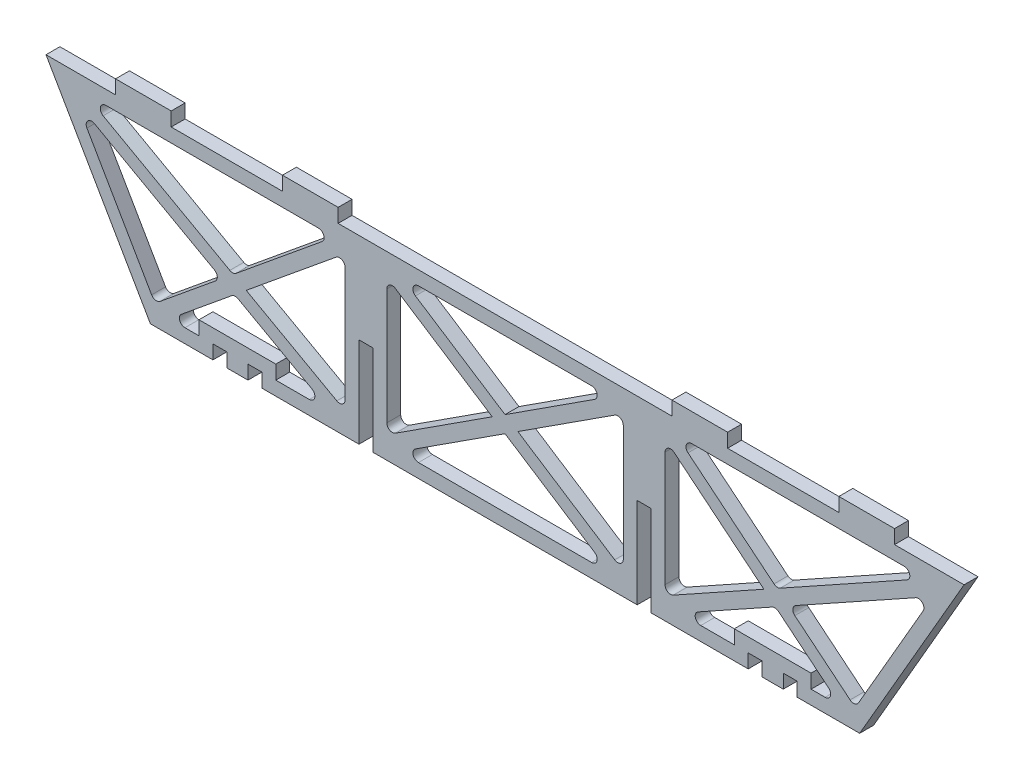
SolidWorks part; units mm, degrees
ref_plane "Front Plane" through (0, 0, 0) normal (0, 0, 1) x (1, 0, 0)
ref_plane "Top Plane" through (0, 0, 0) normal (0, 1, 0) x (1, 0, 0)
ref_plane "Right Plane" through (0, 0, 0) normal (1, 0, 0) x (0, 0, -1)
sketch "Sketch1" plane through (0, 0, 0) normal (0, 0, 1) x (1, 0, 0)
  line L0 (47.6603, 0) -> (76.2, 0)
  line L1 (0, 0) -> (0, 82.55) construction
  line L2 (0, 82.55) -> (31.75, 82.55)
  line L3 (98.552, 0) -> (142.875, 0)
  line L4 (0, 82.55) -> (47.6603, 0)
  line L5 (209.55, 82.55) -> (209.55, 0) construction
  line L6 (146.05, 82.55) -> (146.05, 41.275) construction
  line L7 (0, 0) -> (47.6603, 0) construction
  line L8 (142.875, 0) -> (142.875, 41.275)
  line L9 (31.75, 82.55) -> (31.75, 88.9)
  line L10 (31.75, 88.9) -> (57.15, 88.9)
  line L11 (57.15, 88.9) -> (57.15, 82.55)
  line L12 (57.15, 82.55) -> (107.95, 82.55)
  line L13 (107.95, 82.55) -> (107.95, 88.9)
  line L14 (107.95, 88.9) -> (133.35, 88.9)
  line L15 (133.35, 88.9) -> (133.35, 82.55)
  line L16 (133.35, 82.55) -> (209.55, 82.55)
  line L17 (170.0204, 6.35) -> (249.0796, 6.35)
  line L18 (155.575, 14.8006) -> (155.575, 67.7494)
  line L19 (170.0204, 76.2) -> (249.0796, 76.2)
  line L20 (136.525, 14.3036) -> (136.525, 66.7274)
  line L21 (104.902, 6.35) -> (120.207, 6.35)
  line L22 (104.902, 12.7) -> (104.902, 6.35)
  line L23 (69.85, 12.7) -> (104.902, 12.7)
  line L24 (69.85, 12.7) -> (69.85, 6.35)
  line L25 (76.2, 0) -> (76.2, 6.35)
  line L26 (76.2, 6.35) -> (82.55, 6.35)
  line L27 (82.55, 6.35) -> (82.55, 0)
  line L28 (82.55, 0) -> (92.202, 0)
  line L29 (92.202, 0) -> (92.202, 6.35)
  line L30 (92.202, 6.35) -> (98.552, 6.35)
  line L31 (98.552, 6.35) -> (98.552, 0)
  line L32 (10.9985, 76.2) -> (136.525, 6.35) construction
  line L33 (51.3264, 6.35) -> (136.525, 76.2) construction
  line L34 (155.575, 6.35) -> (209.55, 41.275) construction
  line L35 (155.575, 76.2) -> (209.55, 41.275) construction
  line L36 (63.4386, 6.35) -> (69.85, 6.35)
  line L37 (18.6834, 62.8895) -> (48.2215, 11.728)
  line L38 (27.3165, 76.2) -> (124.4128, 76.2)
  line L39 (26.0814, 71.4405) -> (83.9206, 39.2555)
  line L40 (142.875, 41.275) -> (149.225, 41.275)
  line L41 (22.1181, 66.379) -> (76.8867, 35.9027)
  line L42 (126.0232, 71.6958) -> (86.766, 39.5108)
  line L43 (149.225, 0) -> (149.225, 41.275)
  line L44 (149.225, 0) -> (209.55, 0)
  line L45 (61.8282, 10.8542) -> (84.7804, 29.6715)
  line L46 (159.4949, 12.6681) -> (203.7056, 41.275)
  line L47 (159.4949, 69.8819) -> (203.7056, 41.275)
  line L48 (168.6406, 71.5275) -> (209.55, 45.0567)
  line L49 (168.6406, 11.0225) -> (209.55, 37.4933)
  line L50 (136.525, 6.35) -> (136.525, 47.625) construction
  line L51 (91.3963, 35.0956) -> (132.3746, 68.6917)
  line L52 (136.525, 47.625) -> (155.575, 47.625) construction
  line L53 (155.575, 6.35) -> (155.575, 47.625) construction
  line L54 (51.3264, 6.35) -> (69.85, 6.35) construction
  line L55 (10.9985, 76.2) -> (51.3264, 6.35) construction
  line L56 (77.262, 31.7189) -> (52.0316, 11.0337)
  line L57 (91.3963, 35.0956) -> (132.7499, 12.0841)
  line L58 (87.6258, 29.9268) -> (121.4421, 11.1095)
  line L59 (136.525, 66.7274) -> (136.525, 76.2) construction
  line L60 (114.3, 82.55) -> (127, 82.55) construction
  line L61 (114.3, 76.2) -> (114.3, 82.55) construction
  line L62 (127, 82.55) -> (127, 76.2) construction
  line L63 (38.1, 82.55) -> (50.8, 82.55) construction
  line L64 (50.8, 82.55) -> (50.8, 76.2) construction
  line L65 (38.1, 76.2) -> (38.1, 82.55) construction
  line L66 (50.8, 76.2) -> (114.3, 76.2) construction
  line L67 (10.9985, 76.2) -> (38.1, 76.2) construction
  line L68 (127, 76.2) -> (209.55, 76.2) construction
  line L69 (87.376, 12.7) -> (104.902, 12.7) construction
  line L70 (87.376, 12.7) -> (87.376, 12.7) construction
  line L71 (87.376, 12.7) -> (87.376, 12.7) construction
  line L72 (87.376, 12.7) -> (87.376, 12.7) construction
  line L73 (69.85, 12.7) -> (87.376, 12.7) construction
  line L74 (104.902, 6.35) -> (136.525, 6.35) construction
  line L75 (155.575, 6.35) -> (209.55, 6.35) construction
  line L76 (136.525, 76.2) -> (124.4128, 76.2) construction
  line L77 (27.3165, 76.2) -> (10.9985, 76.2) construction
  line L78 (10.9985, 76.2) -> (18.6834, 62.8895) construction
  line L79 (104.902, 12.7) -> (104.902, 6.35) construction
  line L80 (69.85, 6.35) -> (69.85, 12.7) construction
  line L81 (155.575, 76.2) -> (170.0204, 76.2) construction
  line L82 (155.575, 76.2) -> (155.575, 67.7494) construction
  line L83 (331.4742, 29.9268) -> (297.6579, 11.1095)
  line L84 (327.7037, 35.0956) -> (286.3501, 12.0841)
  line L85 (341.838, 31.7189) -> (367.0684, 11.0337)
  line L86 (327.7037, 35.0956) -> (286.7254, 68.6917)
  line L87 (250.4594, 11.0225) -> (209.55, 37.4933)
  line L88 (250.4594, 71.5275) -> (209.55, 45.0567)
  line L89 (259.6051, 69.8819) -> (215.3944, 41.275)
  line L90 (259.6051, 12.6681) -> (215.3944, 41.275)
  line L91 (357.2718, 10.8542) -> (334.3196, 29.6715)
  line L92 (269.875, 0) -> (209.55, 0)
  line L93 (269.875, 0) -> (269.875, 41.275)
  line L94 (293.0768, 71.6958) -> (332.334, 39.5108)
  line L95 (396.9819, 66.379) -> (342.2133, 35.9027)
  line L96 (276.225, 41.275) -> (269.875, 41.275)
  line L97 (393.0186, 71.4405) -> (335.1794, 39.2555)
  line L98 (391.7835, 76.2) -> (294.6872, 76.2)
  line L99 (400.4166, 62.8895) -> (370.8785, 11.728)
  line L100 (355.6614, 6.35) -> (349.25, 6.35)
  line L101 (320.548, 6.35) -> (320.548, 0)
  line L102 (326.898, 6.35) -> (320.548, 6.35)
  line L103 (326.898, 0) -> (326.898, 6.35)
  line L104 (336.55, 0) -> (326.898, 0)
  line L105 (336.55, 6.35) -> (336.55, 0)
  line L106 (342.9, 6.35) -> (336.55, 6.35)
  line L107 (342.9, 0) -> (342.9, 6.35)
  line L108 (349.25, 12.7) -> (349.25, 6.35)
  line L109 (349.25, 12.7) -> (314.198, 12.7)
  line L110 (314.198, 12.7) -> (314.198, 6.35)
  line L111 (314.198, 6.35) -> (298.893, 6.35)
  line L112 (282.575, 14.3036) -> (282.575, 66.7274)
  line L113 (263.525, 14.8006) -> (263.525, 67.7494)
  line L114 (285.75, 82.55) -> (209.55, 82.55)
  line L115 (285.75, 88.9) -> (285.75, 82.55)
  line L116 (311.15, 88.9) -> (285.75, 88.9)
  line L117 (311.15, 82.55) -> (311.15, 88.9)
  line L118 (361.95, 82.55) -> (311.15, 82.55)
  line L119 (361.95, 88.9) -> (361.95, 82.55)
  line L120 (387.35, 88.9) -> (361.95, 88.9)
  line L121 (387.35, 82.55) -> (387.35, 88.9)
  line L122 (276.225, 0) -> (276.225, 41.275)
  line L123 (419.1, 82.55) -> (371.4397, 0)
  line L124 (320.548, 0) -> (276.225, 0)
  line L125 (419.1, 82.55) -> (387.35, 82.55)
  line L126 (371.4397, 0) -> (342.9, 0)
  line L127 (155.575, 14.8006) -> (155.575, 6.35) construction
  line L128 (155.575, 6.35) -> (170.0204, 6.35) construction
  line L129 (48.2215, 11.728) -> (51.3264, 6.35) construction
  line L130 (51.3264, 6.35) -> (63.4386, 6.35) construction
  line L131 (120.207, 6.35) -> (136.525, 6.35) construction
  line L132 (136.525, 6.35) -> (136.525, 14.3036) construction
  arc A0 (27.3165, 76.2) -> (26.0814, 71.4405) centre (27.3165, 73.66) ccw
  arc A1 (18.6834, 62.8895) -> (22.1181, 66.379) centre (20.8831, 64.1595) cw
  arc A2 (48.2215, 11.728) -> (52.0316, 11.0337) centre (50.4212, 12.998) ccw
  arc A3 (63.4386, 6.35) -> (61.8282, 10.8542) centre (63.4386, 8.89) cw
  arc A4 (86.766, 39.5108) -> (83.9206, 39.2555) centre (85.1556, 41.475) cw
  arc A5 (76.8867, 35.9027) -> (77.262, 31.7189) centre (75.6516, 33.6832) cw
  arc A6 (87.6258, 29.9268) -> (84.7804, 29.6715) centre (86.3908, 27.7073) ccw
  arc A7 (121.4421, 11.1095) -> (120.207, 6.35) centre (120.207, 8.89) cw
  arc A8 (136.525, 14.3036) -> (132.7499, 12.0841) centre (133.985, 14.3036) cw
  arc A9 (136.525, 66.7274) -> (132.3746, 68.6917) centre (133.985, 66.7274) ccw
  arc A10 (124.4128, 76.2) -> (126.0232, 71.6958) centre (124.4128, 73.66) cw
  arc A11 (170.0204, 76.2) -> (168.6406, 71.5275) centre (170.0204, 73.66) ccw
  arc A12 (155.575, 67.7494) -> (159.4949, 69.8819) centre (158.115, 67.7494) cw
  arc A13 (155.575, 14.8006) -> (159.4949, 12.6681) centre (158.115, 14.8006) ccw
  arc A14 (170.0204, 6.35) -> (168.6406, 11.0225) centre (170.0204, 8.89) cw
  arc A15 (249.0796, 6.35) -> (250.4594, 11.0225) centre (249.0796, 8.89) ccw
  arc A16 (263.525, 14.8006) -> (259.6051, 12.6681) centre (260.985, 14.8006) cw
  arc A17 (263.525, 67.7494) -> (259.6051, 69.8819) centre (260.985, 67.7494) ccw
  arc A18 (249.0796, 76.2) -> (250.4594, 71.5275) centre (249.0796, 73.66) cw
  arc A19 (294.6872, 76.2) -> (293.0768, 71.6958) centre (294.6872, 73.66) ccw
  arc A20 (282.575, 66.7274) -> (286.7254, 68.6917) centre (285.115, 66.7274) cw
  arc A21 (282.575, 14.3036) -> (286.3501, 12.0841) centre (285.115, 14.3036) ccw
  arc A22 (297.6579, 11.1095) -> (298.893, 6.35) centre (298.893, 8.89) ccw
  arc A23 (331.4742, 29.9268) -> (334.3196, 29.6715) centre (332.7092, 27.7073) cw
  arc A24 (342.2133, 35.9027) -> (341.838, 31.7189) centre (343.4484, 33.6832) ccw
  arc A25 (332.334, 39.5108) -> (335.1794, 39.2555) centre (333.9444, 41.475) ccw
  arc A26 (355.6614, 6.35) -> (357.2718, 10.8542) centre (355.6614, 8.89) ccw
  arc A27 (370.8785, 11.728) -> (367.0684, 11.0337) centre (368.6788, 12.998) cw
  arc A28 (400.4166, 62.8895) -> (396.9819, 66.379) centre (398.2169, 64.1595) ccw
  arc A29 (391.7835, 76.2) -> (393.0186, 71.4405) centre (391.7835, 73.66) cw
  point P45 (146.05, 41.275)
  point P103 (209.55, 6.35)
  point P184 (209.55, 76.2)
  point P210 (273.05, 41.275)
  dimension "D26" = 3.175
  dimension "D27" = 2.54
  dimension "D1" = 60
  dimension "D2" = 82.55
  dimension "D3" = 6.35
  dimension "D4" = 25.4
  dimension "D5" = 25.4
  dimension "D6" = 6.35
  dimension "D7" = 6.35
  dimension "D8" = 76.2
  dimension "D9" = 9.652
  dimension "D10" = 6.35
  dimension "D11" = 6.35
  dimension "D12" = 41.275
  dimension "D13" = 209.55
  dimension "D14" = 76.2
  dimension "D15" = 152.4
  dimension "D16" = 6.35
  dimension "D17" = 6.35
  dimension "D18" = 63.5
  dimension "D19" = 3.175
  dimension "D20" = 3.175
  dimension "D21" = 3.175
  dimension "D22" = 3.175
  dimension "D23" = 3.175
  dimension "D24" = 3.175
  dimension "D25" = 3.175
extrude "Extrude2" add sketch "Sketch1" along normal blind 6.35
